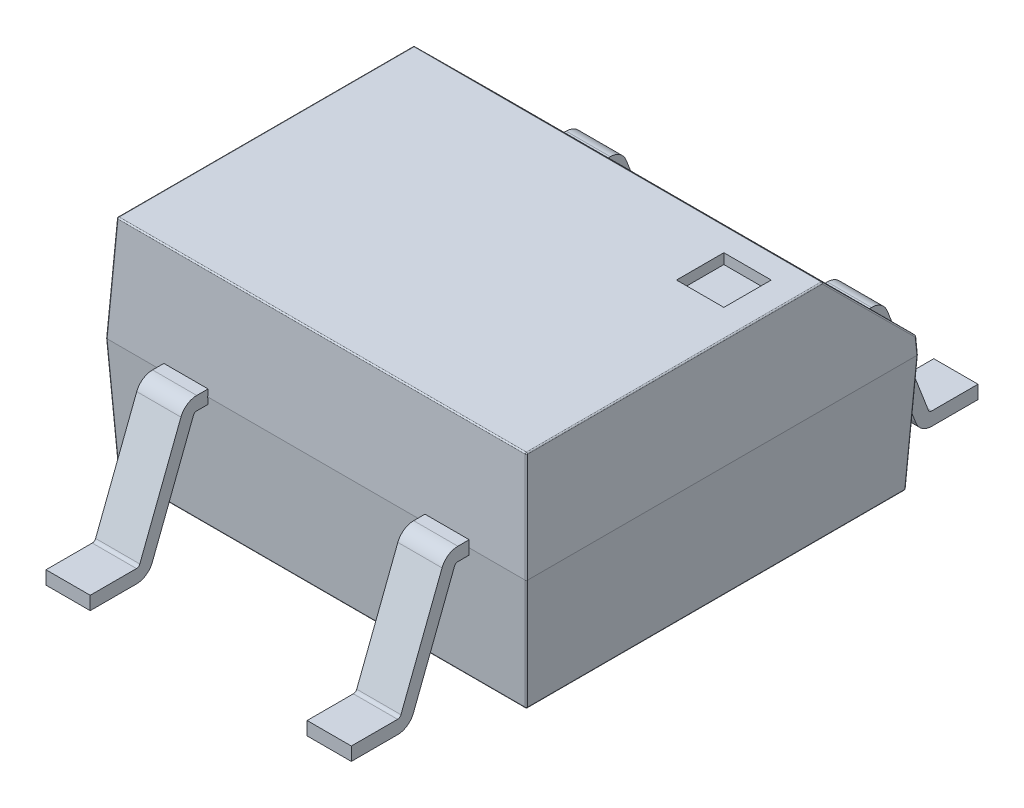
SolidWorks part; units mm, degrees
ref_plane "Front Plane" through (0, 0, 0) normal (0, 0, 1) x (1, 0, 0)
ref_plane "Top Plane" through (0, 0, 0) normal (0, 1, 0) x (1, 0, 0)
ref_plane "Right Plane" through (0, 0, 0) normal (1, 0, 0) x (0, 0, -1)
sketch "Sketch1" plane through (0, 0, 0) normal (0, 1, 0) x (1, 0, 0)
  line L0 (0, 0.9317) -> (0, -0.9273) construction
  line L1 (-1.6279, 0) -> (1.65, 0) construction
  line L3 (-2.045, 1.905) -> (2.045, 1.905)
  line L4 (-2.045, 1.905) -> (-2.045, -1.905)
  line L5 (-2.045, -1.905) -> (2.045, -1.905)
  line L6 (2.045, 1.905) -> (2.045, -1.905)
  dimension "D1" = 4.09
  dimension "D2" = 3.81
extrude "Extrude1" add sketch "Sketch1" along normal blind 1.02 draft 3 and the other way blind 1.14 draft 3
fillet "Fillet1" radius 0.0125 16 edges at (1.9853, -1.14, 0) (-2.0183, 0.51, -1.8783) (0, -1.14, -1.8453) (-2.0183, 0.51, 1.8783) (2.0183, 0.51, 1.8783) (2.0183, 0.51, -1.8783) (-1.9915, 1.02, 0) (0, 1.02, 1.8515) (1.9915, 1.02, 0) (0, 1.02, -1.8515) (-1.9853, -1.14, 0) (0, -1.14, 1.8453) (-2.0151, -0.57, -1.8751) (2.0151, -0.57, -1.8751) (2.0151, -0.57, 1.8751) (-2.0151, -0.57, 1.8751)
ref_plane "Plane1" through (1.27, 0, 0) normal (1, 0, 0) x (0, 0, -1)
sketch "Sketch3" plane through (1.27, 0, 0) normal (1, 0, 0) x (0, 0, -1)
  line L0 (-1.3536, -1.165) -> (1.2261, -1.165) construction
  line L1 (-1.8453, -1.14) -> (1.8453, -1.14) construction
  line L2 (-1.9, 0) -> (-2.0116, 0)
  line L3 (-1.8925, 0) -> (1.8925, 0) construction
  line L4 (-2.1049, -0.064) -> (-2.5049, -1.101)
  line L5 (-2.5982, -1.165) -> (-3.048, -1.165)
  arc A0 (-2.1049, -0.064) -> (-2.0116, 0) centre (-2.0116, -0.1) cw
  arc A1 (-2.5982, -1.165) -> (-2.5049, -1.101) centre (-2.5982, -1.065) ccw
  point P15 (-2.5295, -1.165)
  dimension "D4" = 0.1
  dimension "D1" = 0.025
  dimension "D2" = 3.048
  dimension "D3" = 1.9
  dimension "D5" = 0.1116
  dimension "D6" = 0.4
ref_plane "Plane2" through (0, 0, 3.048) normal (0, 0, 1) x (1, 0, 0)
sketch "Sketch4" plane through (0, 0, 3.048) normal (0, 0, 1) x (1, 0, 0)
  line L0 (1.27, -1.2491) -> (1.27, -1.0809) construction
  line L1 (0.6938, -1.165) -> (1.8462, -1.165) construction
  line L3 (1.055, -1.1) -> (1.485, -1.1)
  line L4 (1.055, -1.1) -> (1.055, -1.23)
  line L5 (1.055, -1.23) -> (1.485, -1.23)
  line L6 (1.485, -1.1) -> (1.485, -1.23)
  dimension "D2" = 0.13
  dimension "D3" = 0.43
sweep "Sweep2" add profiles "Sketch4" path "Sketch3"
mirror "Espelhar1" about plane through (0, 0, 0) normal (1, 0, 0) of "Sweep2"
mirror "Espelhar2" about plane through (0, 0, 0) normal (0, 0, 1) of "Espelhar1", "Sweep2"
sketch "Esboço1" plane through (0, 0, 0) normal (1, 0, 0) x (0, 0, -1)
  line L0 (1.9444, 0.1122) -> (0.9115, 1.1397)
  line L1 (0.9115, 1.1397) -> (1.9444, 1.1397)
  line L2 (1.9444, 1.1397) -> (1.9444, 0.1122)
extrude "Corte-extrusão1" cut sketch "Esboço1" against normal mid plane 10
fillet "Filete2" radius 0.0125 8 edges at (-2.0141, 0.5905, -1.4636) (-2.0328, 0.1635, -1.8928) (0, 0.1596, -1.8966) (2.0328, 0.1635, -1.8928) (2.0141, 0.5905, -1.4636) (1.9883, 1.0166, -1.0353) (0, 1.02, -1.0318) (-1.9883, 1.0166, -1.0353)
sketch "Esboço2" plane through (0, 1.02, 0) normal (0, 1, 0) x (1, 0, 0)
  line L1 (1.7219, 0.339) -> (1.2611, 0.339)
  line L2 (1.7219, 0.339) -> (1.7219, 0.7998)
  line L3 (1.7219, 0.7998) -> (1.2611, 0.7998)
  line L4 (1.2611, 0.339) -> (1.2611, 0.7998)
extrude "Corte-extrusão2" cut sketch "Esboço2" against normal blind 0.1
